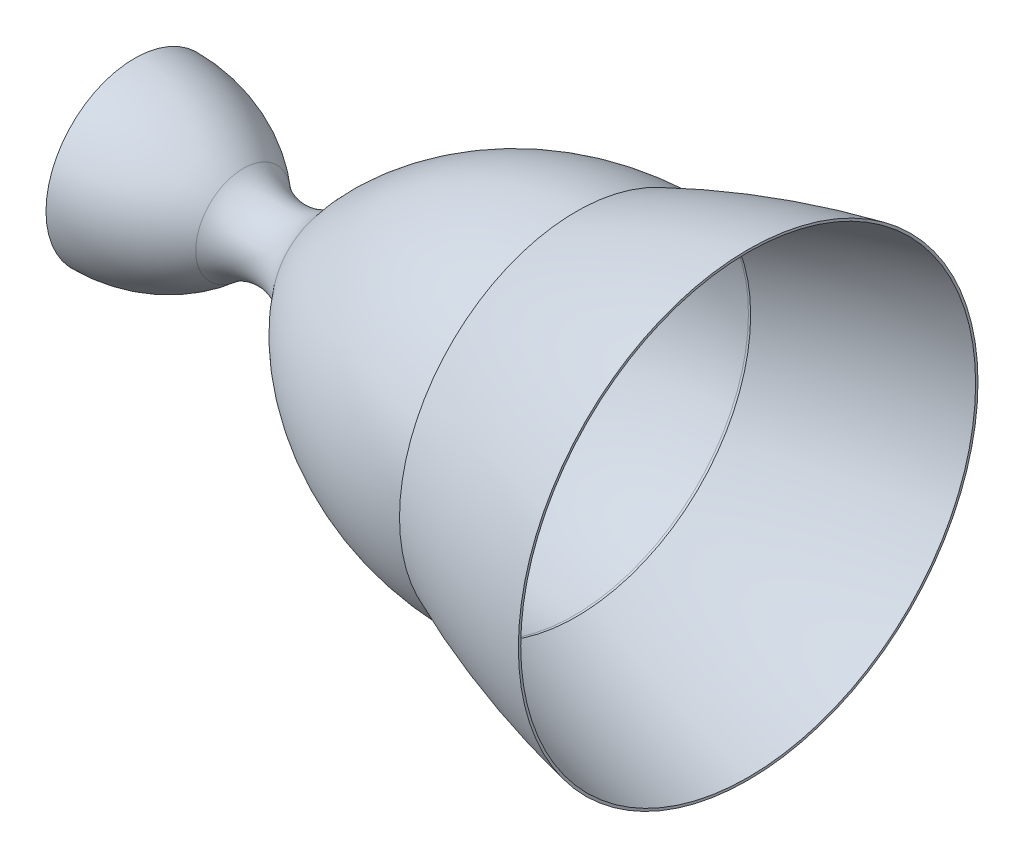
SolidWorks part; units mm, degrees
ref_plane "Alzado" through (0, 0, 0) normal (0, 0, 1) x (1, 0, 0)
ref_plane "Planta" through (0, 0, 0) normal (0, 1, 0) x (1, 0, 0)
ref_plane "Vista lateral" through (0, 0, 0) normal (1, 0, 0) x (0, 0, -1)
sketch "Croquis1" plane through (0, 0, 0) normal (0, 0, 1) x (1, 0, 0)
  line L0 (0, 0) -> (200, 0)
  line L6 (199, 78.9185) -> (200, 78.9185)
  line L10 (1, 38.9153) -> (0, 38.9153)
  line L11 (0, 38.9153) -> (0, 40)
  line L16 (277.796, 102.9388) -> (277.796, 104.0203)
  arc A1 (49.2965, 21.5231) -> (0, 40) centre (0, -35) ccw
  arc A2 (49.2965, 21.5231) -> (87.5619, 25.1727) centre (66.7, 41.4778) ccw
  arc A3 (200, 80) -> (87.5619, 25.1727) centre (200, -62.706) ccw
  arc A5 (48.588, 20.7107) -> (88.4112, 24.5089) centre (66.7, 41.4778) ccw
  arc A6 (199, 78.9185) -> (88.4112, 24.5089) centre (200, -62.706) ccw
  arc A7 (277.796, 104.0203) -> (200, 80) centre (356.2925, -288.2019) ccw
  arc A8 (48.588, 20.7107) -> (1, 38.9153) centre (0, -35) ccw
  arc A9 (277.796, 102.9388) -> (200, 78.9185) centre (356.2925, -289.2834) ccw
  point P5 (0, 0)
  point P9 (0, 0)
  dimension "D6" = 150
  dimension "D4" = 800
  dimension "D7" = 800
  dimension "D1" = 200
  dimension "D2" = 40
revolve "Revolución4" add sketch "Croquis1" angle 360 about L0
